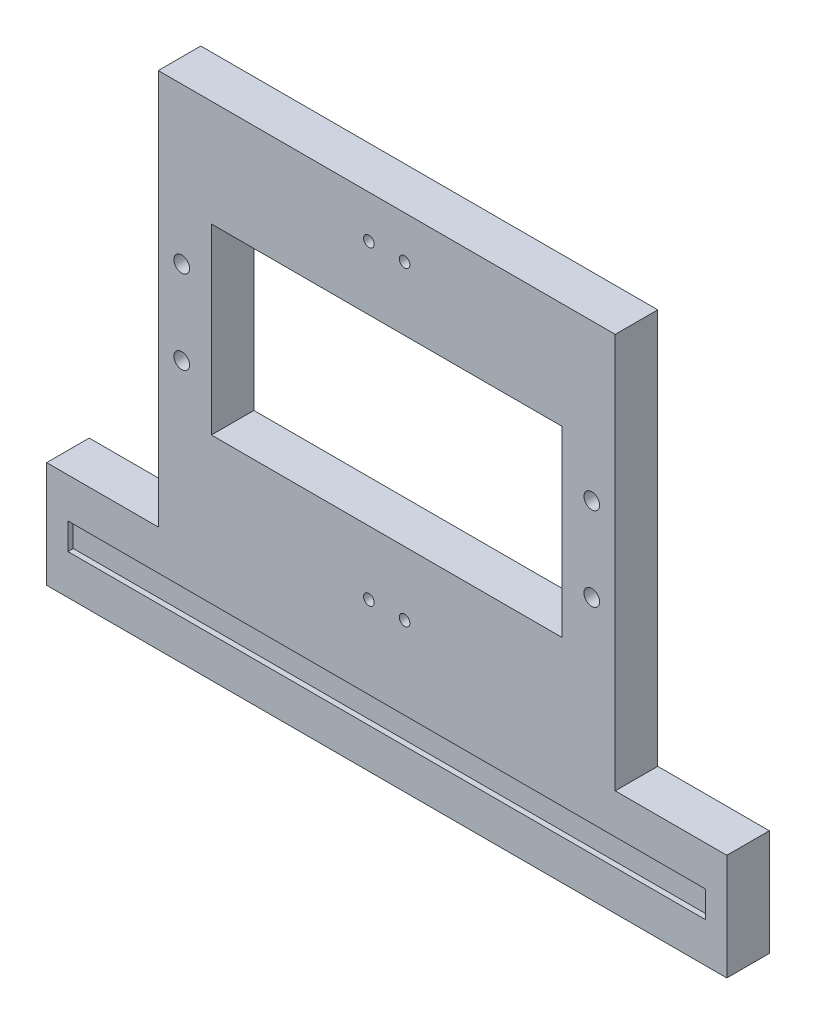
SolidWorks part; units mm, degrees
ref_plane "Front Plane" through (0, 0, 0) normal (0, 0, 1) x (1, 0, 0)
ref_plane "Top Plane" through (0, 0, 0) normal (0, 1, 0) x (1, 0, 0)
ref_plane "Right Plane" through (0, 0, 0) normal (1, 0, 0) x (0, 0, -1)
sketch "Sketch1" plane through (0, 0, 0) normal (0, 0, 1) x (1, 0, 0)
  line L1 (0, 0) -> (54.61, 0)
  line L2 (0, 0) -> (0, 47.244)
  line L3 (0, 47.244) -> (54.61, 47.244)
  line L4 (54.61, 0) -> (54.61, 47.244)
  line L5 (6.35, 12.7) -> (48.26, 12.7)
  line L6 (6.35, 12.7) -> (6.35, 34.544)
  line L7 (6.35, 34.544) -> (48.26, 34.544)
  line L8 (48.26, 12.7) -> (48.26, 34.544)
  dimension "D1" = 41.91
  dimension "D2" = 21.844
  dimension "D3" = 6.35
  dimension "D4" = 6.35
  dimension "D5" = 12.7
  dimension "D6" = 12.7
extrude "Boss-Extrude1" add sketch "Sketch1" along normal blind 5.08
sketch "Sketch2" plane through (0, 0, 5.08) normal (0, 0, 1) x (1, 0, 0)
  line L0 (0, 23.622) -> (54.61, 23.622) construction
  line L1 (2.8054, 28.622) -> (51.8046, 28.622) construction
  line L2 (2.8054, 28.622) -> (2.8054, 18.622) construction
  line L3 (2.8054, 18.622) -> (51.8046, 18.622) construction
  line L4 (51.8046, 28.622) -> (51.8046, 18.622) construction
  line L5 (0, 47.244) -> (0, 0) construction
  line L6 (54.61, 0) -> (54.61, 47.244) construction
  line L7 (2.8054, 23.622) -> (51.8046, 23.622) construction
  line L8 (27.305, 28.622) -> (27.305, 18.622) construction
  line L9 (27.305, 47.244) -> (27.305, 0) construction
  line L10 (54.61, 47.244) -> (0, 47.244) construction
  line L11 (0, 0) -> (54.61, 0) construction
  line L12 (25.1752, 42.164) -> (29.4348, 42.164) construction
  line L13 (29.4348, 42.164) -> (29.4348, 5.08) construction
  line L14 (29.4348, 5.08) -> (25.1752, 5.08) construction
  line L15 (25.1752, 5.08) -> (25.1752, 42.164) construction
  line L16 (48.26, 34.544) -> (6.35, 34.544) construction
  line L17 (6.35, 12.7) -> (48.26, 12.7) construction
  circle A0 centre (2.8054, 28.622) radius 0.936
  circle A1 centre (2.8054, 18.622) radius 0.936
  circle A2 centre (51.8046, 28.622) radius 0.936
  circle A3 centre (51.8046, 18.622) radius 0.936
  circle A4 centre (25.1752, 5.08) radius 0.635
  circle A5 centre (29.4348, 5.08) radius 0.635
  circle A6 centre (29.4348, 42.164) radius 0.635
  circle A7 centre (25.1752, 42.164) radius 0.635
  point P16 (2.8054, 27.686)
  point P17 (2.8054, 19.558)
  dimension "D2" = 8.128
  dimension "D4" = 1.872
  dimension "D5" = 1.27
  dimension "D1" = 10
  dimension "D3" = 48.9991
  dimension "D6" = 4.2596
  dimension "D7" = 2.1298
  dimension "D8" = 7.62
  dimension "D9" = 7.62
extrude "Cut-Extrude1" cut sketch "Sketch2" against normal through all
sketch "Sketch8" plane through (0, 0, 5.08) normal (0, 0, 1) x (1, 0, 0)
  line L0 (0, 0) -> (-13.335, 0)
  line L1 (-13.335, 0) -> (-13.335, -12.7)
  line L2 (-13.335, -12.7) -> (67.945, -12.7)
  line L3 (67.945, -12.7) -> (67.945, 0)
  line L4 (67.945, 0) -> (54.61, 0)
  line L5 (54.61, 0) -> (54.61, 47.244) construction
  line L6 (0, 0) -> (54.61, 0)
  dimension "D1" = 81.28
  dimension "D2" = 12.7
extrude "Boss-Extrude3" add sketch "Sketch8" against normal up to surface (5.08 mm away) up to face at (25.8102, 42.164, 0)
sketch "Sketch9" plane through (0, 0, 5.08) normal (0, 0, 1) x (1, 0, 0)
  line L0 (-10.795, -7.9375) -> (-13.335, -7.9375) construction
  line L1 (-10.795, -4.7625) -> (65.405, -4.7625)
  line L2 (-10.795, -4.7625) -> (-10.795, -7.9375)
  line L3 (-10.795, -7.9375) -> (65.405, -7.9375)
  line L4 (65.405, -4.7625) -> (65.405, -7.9375)
  line L5 (-13.335, 0) -> (-13.335, -12.7) construction
  line L6 (65.405, -7.9375) -> (67.945, -7.9375) construction
  line L7 (67.945, -12.7) -> (67.945, 0) construction
  line L8 (-10.795, -7.9375) -> (-10.795, -12.7) construction
  line L9 (-13.335, -12.7) -> (67.945, -12.7) construction
  line L10 (-10.795, -4.7625) -> (-10.795, 0) construction
  line L11 (0, 0) -> (-13.335, 0) construction
  dimension "D1" = 3.175
  dimension "D2" = 76.2
extrude "Cut-Extrude2" cut sketch "Sketch9" against normal blind 0.635
equation "\"D7@Sketch2\"=\"D6@Sketch2\"/2"
